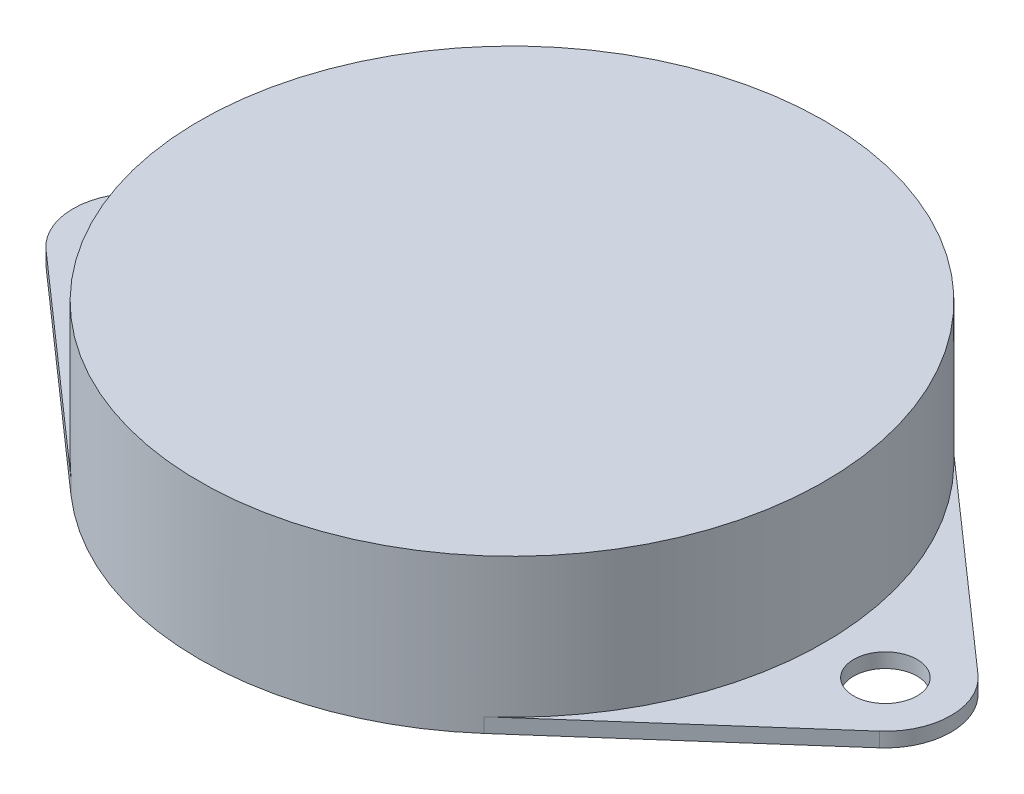
SolidWorks part; units mm, degrees
ref_plane "Front Plane" through (0, 0, 0) normal (0, 0, 1) x (1, 0, 0)
ref_plane "Top Plane" through (0, 0, 0) normal (0, 1, 0) x (1, 0, 0)
ref_plane "Right Plane" through (0, 0, 0) normal (1, 0, 0) x (0, 0, -1)
sketch "Sketch1" plane through (0, 0, 0) normal (0, 1, 0) x (1, 0, 0)
  line L0 (0, 31.408) -> (0, -32.2346) construction
  line L1 (-39.26, 0) -> (36.9182, 0) construction
  line L2 (-23.3902, 2.763) -> (-11.5968, 13.1575)
  line L3 (-23.3902, -2.763) -> (-11.5968, -13.1575)
  line L4 (23.3902, 2.763) -> (11.5968, 13.1575)
  line L5 (23.3902, -2.763) -> (11.5968, -13.1575)
  arc A0 (-11.5968, -13.1575) -> (11.5968, -13.1575) centre (0, 0) ccw
  arc A1 (-23.3902, 2.763) -> (-23.3902, -2.763) centre (-20.955, 0) ccw
  circle A2 centre (-20.955, 0) radius 1.778
  arc A3 (23.3902, 2.763) -> (23.3902, -2.763) centre (20.955, 0) cw
  circle A4 centre (20.955, 0) radius 1.778
  arc A5 (11.5968, 13.1575) -> (-11.5968, 13.1575) centre (0, 0) ccw
  point P18 (-24.638, 0)
  point P19 (24.638, 0)
  point P20 (-23.0338, 3.4635)
  dimension "D1" = 17.5387
  dimension "D2" = 3.556
  dimension "D3" = 49.276
  dimension "D4" = 41.91
extrude "Boss-Extrude1" add sketch "Sketch1" along normal blind 0.8128
sketch "Sketch2" plane through (0, 0.8128, 0) normal (0, 1, 0) x (1, 0, 0)
  circle A0 centre (0, 0) radius 17.5387
  arc A1 (-11.5968, -13.1575) -> (11.5968, -13.1575) centre (0, 0) ccw construction
extrude "Boss-Extrude2" add sketch "Sketch2" along normal offset from surface (7.8232 mm away) 8.636 up to face at (-20.955, 0, 1.778)
sketch "Sketch3" plane through (0, 0, 0) normal (0, 1, 0) x (1, 0, 0)
  circle A0 centre (0, 0) radius 5.0165
  circle A1 centre (0, 0) radius 17.5387 construction
  point P2 (0, 0)
  point P3 (-9.1227, -1.1377)
  dimension "D1" = 10.033
extrude "Boss-Extrude3" add sketch "Sketch3" against normal blind 1.524
sketch "Sketch5" plane through (0, -1.524, 0) normal (0, -1, 0) x (1, 0, 0)
  circle A0 centre (0, 0) radius 1.016
  dimension "D1" = 2.032
extrude "Boss-Extrude4" add sketch "Sketch5" along normal blind 3.81
sketch "Sketch6" plane through (0, -5.334, 0) normal (0, -1, 0) x (1, 0, 0)
  circle A0 centre (0, 0) radius 4.191
  circle A1 centre (0, 0) radius 1.016 construction
  dimension "D1" = 8.382
extrude "Boss-Extrude5" add sketch "Sketch6" along normal offset from surface (3.302 mm away) 17.272 up to face at (0, 8.636, -17.5387)
